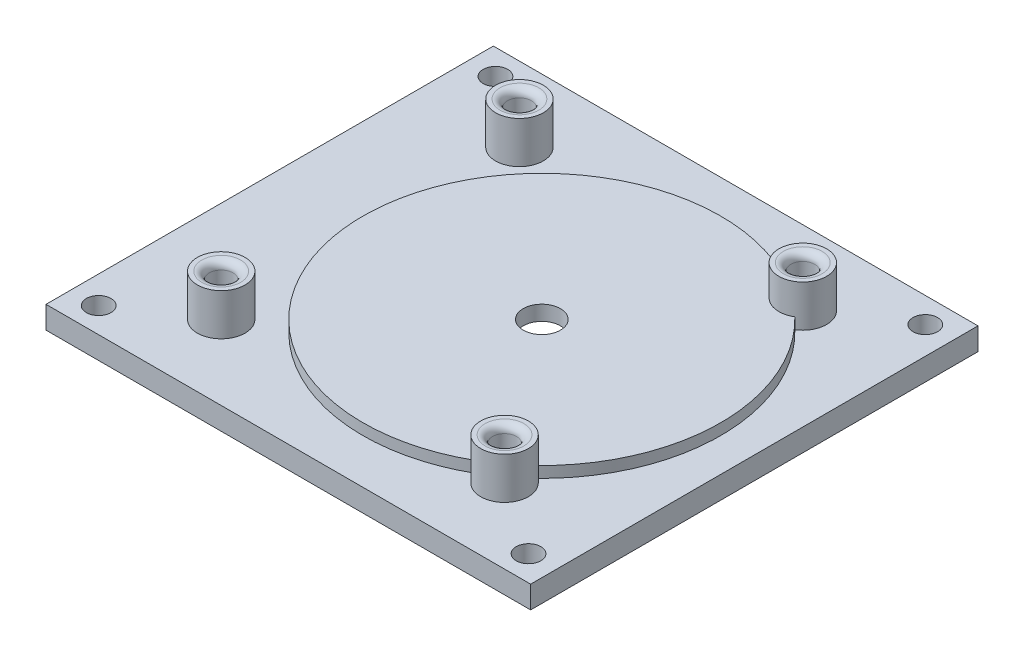
SolidWorks part; units mm, degrees
ref_plane "Front Plane" through (0, 0, 0) normal (0, 0, 1) x (1, 0, 0)
ref_plane "Top Plane" through (0, 0, 0) normal (0, 1, 0) x (1, 0, 0)
ref_plane "Right Plane" through (0, 0, 0) normal (1, 0, 0) x (0, 0, -1)
sketch "Sketch2" plane through (0, 0, 0) normal (0, 1, 0) x (1, 0, 0)
  line L4 (65, 0) -> (0, 0)
  line L5 (0, 0) -> (0, -60)
  line L6 (0, -60) -> (65, -60)
  line L7 (65, -60) -> (65, 0)
  circle A19 centre (3.674, -3.3914) radius 1.65
  circle A20 centre (61.326, -3.3914) radius 1.65
  circle A22 centre (61.326, -56.6086) radius 1.65
  circle A24 centre (3.674, -56.6086) radius 1.65
  point P0 (0, 0)
  point P7 (36.5, -30)
  dimension "D1" = 65
  dimension "D2" = 60
  dimension "D3" = 3.3
  dimension "D4" = 3.3
  dimension "D5" = 3.3
  dimension "D6" = 3.3
  dimension "D7" = 3.674
  dimension "D8" = 3.3914
  dimension "D9" = 30
  dimension "D11" = 3.674
  dimension "D12" = 53.2172
  dimension "D10" = 28.5
extrude "Boss-Extrude1" add sketch "Sketch2" along normal blind 3 separate body
sketch "Sketch3" plane through (0, 3, 0) normal (0, 1, 0) x (1, 0, 0)
  line L0 (0, 0) -> (0, -60) construction
  line L1 (0, -60) -> (65, -60) construction
  circle A0 centre (36.5, -30) radius 24
  dimension "D1" = 48
  dimension "D2" = 36.5
  dimension "D3" = 30
extrude "Boss-Extrude2" add sketch "Sketch3" along normal blind 1.5
sketch "Sketch5" plane through (0, 0, 0) normal (0, 1, 0) x (1, 0, 0)
  circle A0 centre (36.5, -30) radius 19
  dimension "D1" = 38
extrude "Cut-Extrude1" cut sketch "Sketch5" along normal blind 2.5
sketch "Sketch6" plane through (0, 4.5, 0) normal (0, 1, 0) x (1, 0, 0)
  circle A0 centre (36.5, -30) radius 2.5
  dimension "D1" = 5
extrude "Cut-Extrude2" cut sketch "Sketch6" against normal through all
sketch "Sketch7" plane through (0, 3, 0) normal (0, 1, 0) x (1, 0, 0)
  line L0 (65, 0) -> (0, 0) construction
  line L2 (65, -60) -> (65, 0) construction
  circle A0 centre (13.5, -10) radius 1.6
  circle A1 centre (13.5, -10) radius 3.2
  circle A2 centre (13.5, -50) radius 1.6
  circle A3 centre (13.5, -50) radius 3.2
  circle A4 centre (51.5, -10) radius 1.6
  circle A5 centre (51.5, -10) radius 3.2
  circle A6 centre (51.5, -50) radius 1.6
  circle A7 centre (51.5, -50) radius 3.2
  point P12 (0, 0)
  point P13 (0, 0)
  point P14 (0, 0)
  point P15 (0, 0)
  dimension "D1" = 6.4
  dimension "D2" = 6.4
  dimension "D3" = 3.2
  dimension "D4" = 3.2
  dimension "D5" = 6.4
  dimension "D6" = 3.2
  dimension "D7" = 3.2
  dimension "D8" = 6.4
  dimension "D9" = 10
  dimension "D10" = 13.5
  dimension "D11" = 38
  dimension "D12" = 40
extrude "Boss-Extrude3" add sketch "Sketch7" along normal blind 5.6
fillet "Fillet1" radius 1 4 edges at (13.5, 8.6, 11.6) (13.5, 8.6, 51.6) (51.5, 8.6, 51.6) (51.5, 8.6, 11.6)
move or copy body "Body-Move/Copy3" bodies to move or copy 109 placed by mates yes parameters "D1"=0, "D2"=0, "D3"=0
